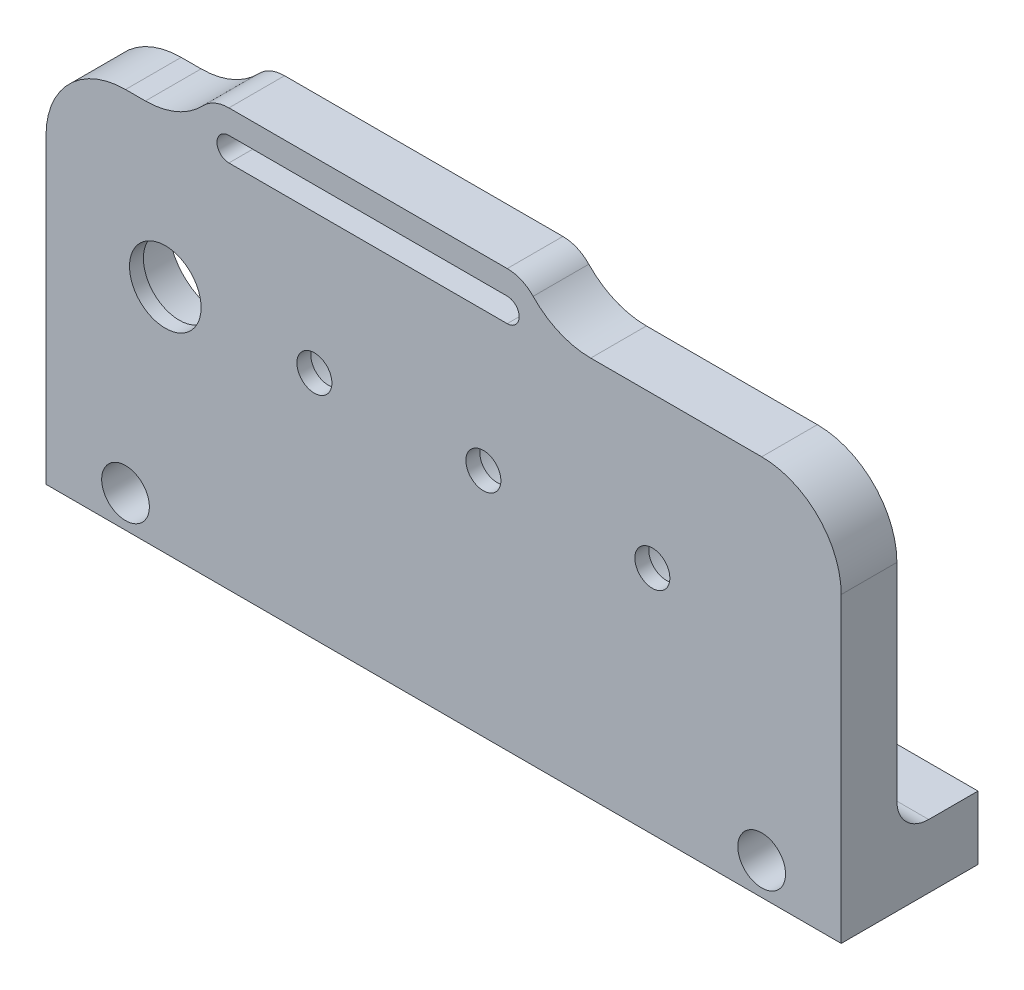
SolidWorks part; units mm, degrees
ref_plane "Front Plane" through (0, 0, 0) normal (0, 0, 1) x (1, 0, 0)
ref_plane "Top Plane" through (0, 0, 0) normal (0, 1, 0) x (1, 0, 0)
ref_plane "Right Plane" through (0, 0, 0) normal (1, 0, 0) x (0, 0, -1)
sketch "Sketch1" plane through (0, 0, 0) normal (0, 0, 1) x (1, 0, 0)
  line L1 (0, 0) -> (100, 0)
  line L2 (0, 0) -> (0, 48)
  line L3 (0, 48) -> (100, 48)
  line L4 (100, 0) -> (100, 48)
  dimension "D1" = 100
  dimension "D2" = 48
extrude "Boss-Extrude1" add sketch "Sketch1" along normal blind 7
sketch "Sketch2" plane through (0, 0, 7) normal (0, 0, 1) x (1, 0, 0)
  line L0 (0, 0) -> (100, 0) construction
  line L1 (0, 48) -> (0, 0) construction
  circle A0 centre (15, 29) radius 4.5
  circle A1 centre (33.75, 29) radius 2.2
  circle A2 centre (55, 29) radius 2.2
  circle A3 centre (76.25, 29) radius 2.2
  dimension "D1" = 4.4
  dimension "D2" = 18.75
  dimension "D3" = 21.25
  dimension "D4" = 21.25
  dimension "D5" = 29
  dimension "D6" = 15
  dimension "D7" = 9
extrude "Cut-Extrude1" cut sketch "Sketch2" against normal up to next
sketch "Sketch3" plane through (0, 0, 0) normal (0, 0, -1) x (-1, 0, 0)
  line L0 (0, 48) -> (0, 0) construction
  line L1 (-100, 0) -> (0, 0)
  line L2 (-100, 0) -> (-100, 8)
  line L3 (-100, 8) -> (0, 8)
  line L4 (0, 0) -> (0, 8)
  dimension "D1" = 8
extrude "Boss-Extrude2" add sketch "Sketch3" along normal blind 10.2
sketch "Sketch4" plane through (0, 0, 0) normal (0, 0, -1) x (-1, 0, 0)
  circle A0 centre (-76.25, 29) radius 6.6
  circle A1 centre (-55, 29) radius 6.6
  circle A2 centre (-33.75, 29) radius 6.6
  circle A3 centre (-15, 29) radius 6.6
  dimension "D1" = 13.2
extrude "Cut-Extrude2" cut sketch "Sketch4" against normal blind 5.25
sketch "Sketch5" plane through (0, 0, 7) normal (0, 0, 1) x (1, 0, 0)
  line L0 (35, 4.0521) -> (65, 4) construction
  line L1 (0, 0) -> (100, 0) construction
  circle A0 centre (35, 4.0521) radius 2.6
  circle A1 centre (65, 4) radius 2.6
  point P6 (50, 0)
  point P7 (50, 4.0261)
  dimension "D1" = 5.2
  dimension "D2" = 30
  dimension "D3" = 4
extrude "Cut-Extrude3" cut sketch "Sketch5" against normal blind 7
sketch "Sketch7" plane through (0, 0, 0) normal (0, 0, 1) x (1, 0, 0)
  circle A0 centre (35, 4.0521) radius 1.5
  circle A1 centre (65, 4) radius 1.5
  dimension "D1" = 3
extrude "Cut-Extrude4" cut sketch "Sketch7" against normal through all
sketch "Sketch8" plane through (0, 0, 7) normal (0, 0, 1) x (1, 0, 0)
  line L0 (10, 4.0521) -> (35, 4.0521) construction
  line L1 (0, 48) -> (0, 0) construction
  line L2 (100, 0) -> (100, 48) construction
  circle A0 centre (10, 4.0521) radius 1.7
  circle A1 centre (90, 4.0521) radius 1.7
  dimension "D1" = 3.4
  dimension "D2" = 10
  dimension "D3" = 10
extrude "Cut-Extrude5" cut sketch "Sketch8" against normal up to next
sketch "Sketch9" plane through (0, 0, 7) normal (0, 0, 1) x (1, 0, 0)
  circle A0 centre (10, 4.0521) radius 3
  circle A1 centre (90, 4.0521) radius 3
  dimension "D1" = 6
extrude "Cut-Extrude6" cut sketch "Sketch9" against normal blind 9
sketch "Sketch10" plane through (0, 0, 7) normal (0, 0, 1) x (1, 0, 0)
  line L0 (23, 48) -> (58, 48) construction
  line L1 (100, 48) -> (0, 48) construction
  line L2 (23, 49.5) -> (58, 49.5)
  line L3 (23, 46.5) -> (58, 46.5)
  line L4 (23, 52.5) -> (58, 52.5)
  line L5 (23, 43.5) -> (58, 43.5)
  line L6 (0, 48) -> (0, 0) construction
  arc A0 (23, 49.5) -> (23, 46.5) centre (23, 48) ccw
  arc A1 (58, 46.5) -> (58, 49.5) centre (58, 48) ccw
  arc A2 (58, 43.5) -> (58, 52.5) centre (58, 48) ccw
  arc A3 (23, 52.5) -> (23, 43.5) centre (23, 48) ccw
  point P4 (40.5, 48)
  dimension "D3" = 35
  dimension "D2" = 3
  dimension "D4" = 23
  dimension "D1" = 3
extrude "Boss-Extrude3" add sketch "Sketch10" against normal up to surface (7 mm away) up to face at (69.65, 29, 0)
sketch "Sketch11" plane through (0, 0, 7) normal (0, 0, 1) x (1, 0, 0)
  line L0 (23, 48) -> (58, 48) construction
  line L1 (59.5, 48) -> (21.5, 48) construction
  line L2 (23, 49.5) -> (58, 49.5)
  line L3 (23, 46.5) -> (58, 46.5)
  arc A0 (23, 49.5) -> (23, 46.5) centre (23, 48) ccw
  arc A1 (58, 46.5) -> (58, 49.5) centre (58, 48) ccw
  point P5 (40.5, 48)
  dimension "D1" = 3
extrude "Cut-Extrude7" cut sketch "Sketch11" against normal up to next
fillet "Fillet1" radius 10 2 edges at (0, 48, 3.5) (100, 48, 3.5)
fillet "Fillet2" radius 10 2 edges at (62.5, 48, 3.5) (18.5, 48, 3.5)
sketch "Sketch12" plane through (0, 0, 7) normal (0, 0, 1) x (1, 0, 0)
  circle A0 centre (35, 4.0521) radius 2.6
  circle A1 centre (65, 4) radius 2.6
  dimension "D1" = 5.2
  dimension "D2" = 5.2
extrude "Boss-Extrude6" add sketch "Sketch12" against normal up to surface (17.2 mm away) up to face at (11.7, 4.0521, -10.2)
fillet "Fillet3" radius 4 1 edges at (50, 8, 0)
